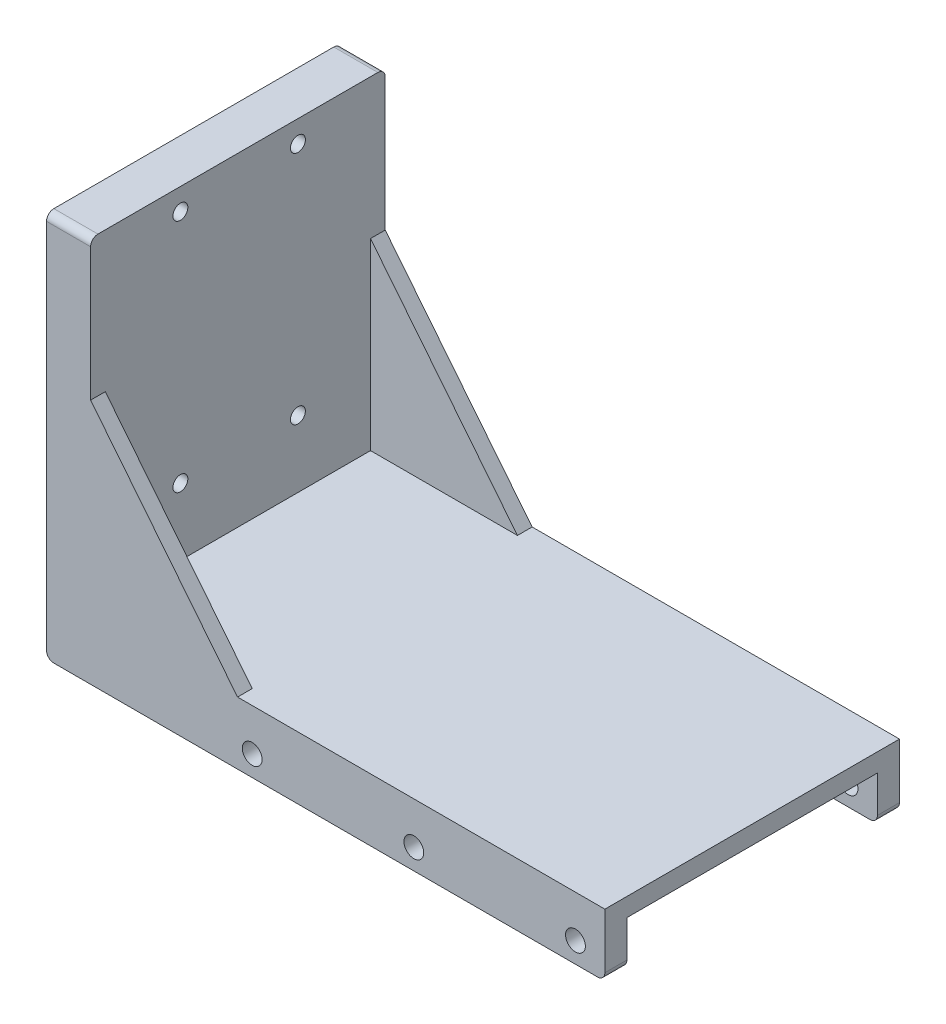
SolidWorks part; units mm, degrees
material "ABS PC"
ref_plane "Front Plane" through (0, 0, 0) normal (0, 0, 1) x (1, 0, 0)
ref_plane "Top Plane" through (0, 0, 0) normal (0, 1, 0) x (1, 0, 0)
ref_plane "Right Plane" through (0, 0, 0) normal (1, 0, 0) x (0, 0, -1)
sketch "Sketch1" plane through (0, 0, 0) normal (0, 0, 1) x (1, 0, 0)
  line L0 (0, 0) -> (0, 52.578)
  line L1 (0, 52.578) -> (6, 52.578)
  line L2 (6, 52.578) -> (6, 8.5)
  line L3 (6, 8.5) -> (76, 8.5)
  line L4 (76, 8.5) -> (76, 0)
  line L5 (76, 0) -> (0, 0)
  dimension "D1" = 52.578
  dimension "D2" = 8.5
  dimension "D3" = 6
  dimension "D4" = 76
extrude "Boss-Extrude1" add sketch "Sketch1" along normal blind 40.1
sketch "Sketch3" plane through (0, 0, 40.1) normal (0, 0, 1) x (1, 0, 0)
  line L0 (0, 52.578) -> (0, 0) construction
  line L1 (0, 0) -> (76, 0) construction
  circle A0 centre (27.996, 2.8) radius 1.35
  circle A1 centre (49.996, 2.8) radius 1.35
  circle A2 centre (71.996, 2.8) radius 1.35
  dimension "D1" = 2.7
  dimension "D4" = 2.7
  dimension "D5" = 2.7
  dimension "D2" = 27.996
  dimension "D3" = 2.8
  dimension "D6" = 22
  dimension "D7" = 22
extrude "Cut-Extrude2" cut sketch "Sketch3" against normal blind 50.8
sketch "Sketch4" plane through (0, 0, 0) normal (-1, 0, 0) x (0, 0, 1)
  line L0 (40.1, 0) -> (0, 0) construction
  line L1 (20.05, 0) -> (20.05, 52.578) construction
  line L2 (40.1, 52.578) -> (0, 52.578) construction
  line L3 (40.1, 52.578) -> (40.1, 0) construction
  line L5 (0, 52.578) -> (0, 0) construction
  circle A0 centre (27.88, 17.6) radius 1.016
  circle A1 centre (11.88, 17.6) radius 1.016
  circle A2 centre (27.88, 49.6) radius 1.016
  circle A3 centre (11.88, 49.6) radius 1.016
  dimension "D1" = 2.032
  dimension "D3" = 2.032
  dimension "D4" = 2.978
  dimension "D2" = 17.6
  dimension "D5" = 12.22
  dimension "D6" = 12.22
  dimension "D7" = 11.88
  dimension "D8" = 11.88
  dimension "D9" = 2.978
extrude "Cut-Extrude3" cut sketch "Sketch4" against normal blind 50.8
sketch "Sketch6" plane through (0, 0, 0) normal (0, -1, 0) x (1, 0, 0)
  line L0 (0, 40.1) -> (76, 40.1) construction
  line L1 (19, 37.1) -> (81.0861, 37.1)
  line L2 (19, 37.1) -> (19, 3)
  line L3 (19, 3) -> (81.0861, 3)
  line L4 (81.0861, 37.1) -> (81.0861, 3)
  line L5 (0, 0) -> (76, 0) construction
  line L6 (0, 40.1) -> (0, 0) construction
  dimension "D1" = 3
  dimension "D2" = 3
  dimension "D3" = 19
extrude "Cut-Extrude4" cut sketch "Sketch6" against normal blind 6
ref_plane "Plane5" through (0, 0, 20.05) normal (0, 0, -1) x (-1, 0, 0)
sketch "Sketch16" plane through (0, 0, 40.1) normal (0, 0, 1) x (1, 0, 0)
  line L0 (6, 8.5) -> (26, 8.5)
  line L1 (76, 8.5) -> (6, 8.5) construction
  line L2 (26, 8.5) -> (6, 33.5)
  line L3 (6, 8.5) -> (6, 52.578) construction
  line L4 (6, 33.5) -> (6, 8.5)
  dimension "D1" = 20
  dimension "D2" = 25
extrude "Boss-Extrude5" add sketch "Sketch16" against normal blind 2
mirror "Mirror2" about plane through (0, 0, 20.05) normal (0, 0, -1) of "Boss-Extrude5"
fillet "Fillet1" radius 1 5 edges at (3, 52.578, 0) (3, 52.578, 40.1) (0, 0, 20.05) (76, 0, 1.5) (76, 0, 38.6)
